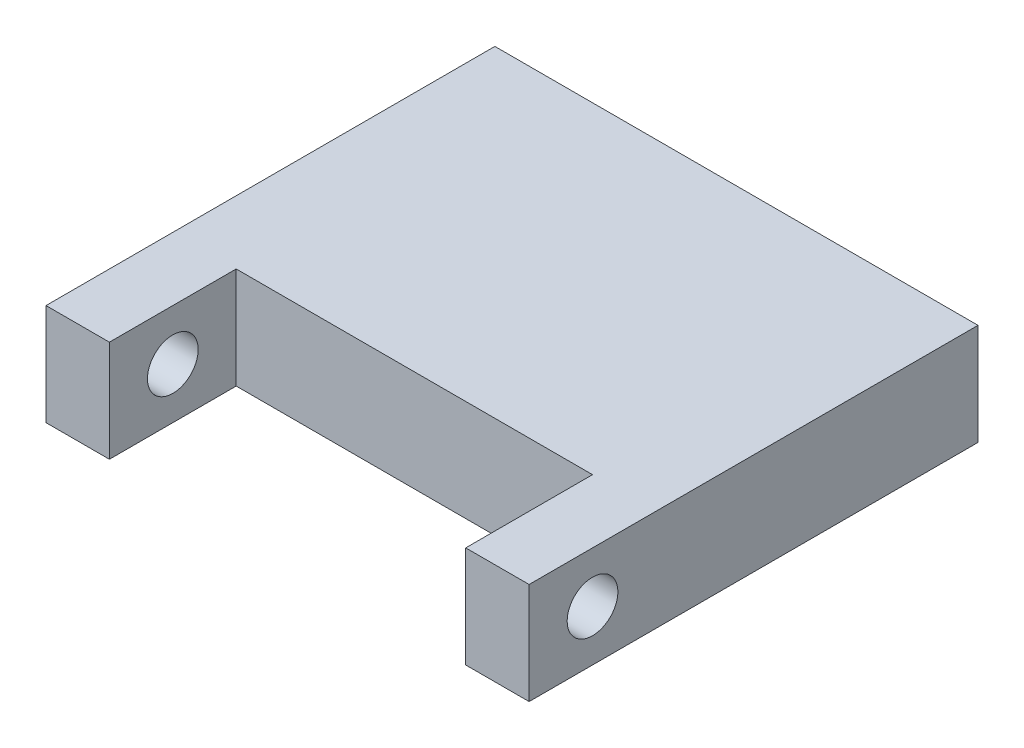
SolidWorks part; units mm, degrees
ref_plane "Front" through (0, 0, 0) normal (0, 0, 1) x (1, 0, 0)
ref_plane "Top" through (0, 0, 0) normal (0, 1, 0) x (1, 0, 0)
ref_plane "Right" through (0, 0, 0) normal (1, 0, 0) x (0, 0, -1)
sketch "Sketch1" plane through (0, 0, 0) normal (0, 1, 0) x (1, 0, 0)
  line L1 (0, 0) -> (38.1, 0)
  line L2 (0, 0) -> (0, 25.4)
  line L3 (0, 25.4) -> (38.1, 25.4)
  line L4 (38.1, 0) -> (38.1, 25.4)
  dimension "D1" = 38.1
  dimension "D2" = 25.4
extrude "Boss-Extrude1" add sketch "Sketch1" along normal blind 8
sketch "Sketch2" plane through (0, 0, 0) normal (0, 0, 1) x (1, 0, 0)
  line L0 (0, 8) -> (38.1, 8) construction
  line L1 (38.1, 0) -> (33.1, 0)
  line L2 (38.1, 0) -> (38.1, 8)
  line L3 (38.1, 8) -> (33.1, 8)
  line L4 (33.1, 0) -> (33.1, 8)
  dimension "D1" = 5
extrude "Boss-Extrude2" add sketch "Sketch2" along normal blind 10
sketch "Sketch3" plane through (33.1, 0, 0) normal (-1, 0, 0) x (0, 0, 1)
  line L0 (10, 4) -> (0, 4)
  line L1 (10, 8) -> (10, 0) construction
  line L2 (0, 8) -> (0, 0) construction
  circle A0 centre (5, 4) radius 2
  dimension "D1" = 5
extrude "Cut-Extrude1" cut sketch "Sketch3" against normal blind 30 contours A0
pattern_linear "LPattern1" count 2 spacing 33.1 along (-1, 0, 0) of "Boss-Extrude2", "Cut-Extrude1"
